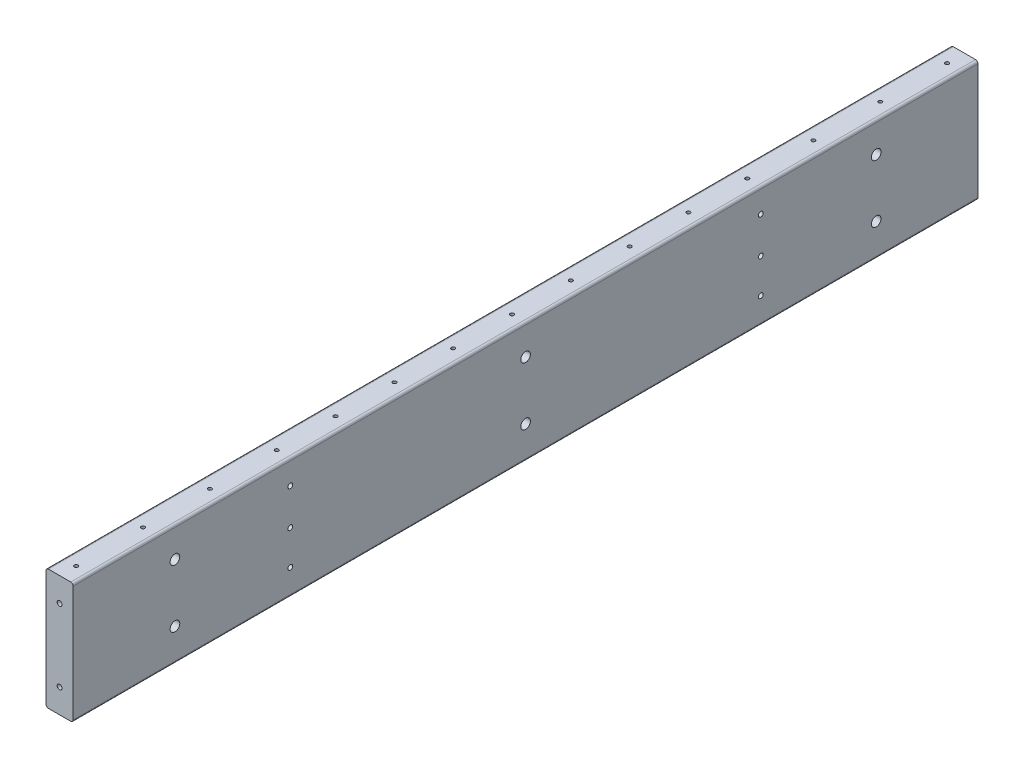
SolidWorks part; units mm, degrees
ref_plane "Front Plane" through (0, 0, 0) normal (0, 0, 1) x (1, 0, 0)
ref_plane "Top Plane" through (0, 0, 0) normal (0, 1, 0) x (1, 0, 0)
ref_plane "Right Plane" through (0, 0, 0) normal (1, 0, 0) x (0, 0, -1)
ref_plane "Plane1" through (-31.1883, 0, 0) normal (-1, 0, 0) x (0, -1, 0)
sketch "Sketch1" plane through (-31.1883, 0, 0) normal (-1, 0, 0) x (0, -1, 0)
  line L0 (-134.2727, 0) -> (65.7273, 0)
  line L1 (65.7273, 0) -> (65.7273, 1500)
  line L2 (65.7273, 1500) -> (-134.2727, 1500)
  line L3 (-134.2727, 1500) -> (-134.2727, 0)
extrude "Boss-Extrude1" add sketch "Sketch1" against normal blind 45
hole_wizard "Ø6.0 (6) Diameter Hole1" positions "Sketch3" profile "Sketch2" hole size "Ø6.0" standard "ANSI Metric"
sketch "Sketch3" plane through (0, 134.2727, 0) normal (0, 1, 0) x (1, 0, 0)
  point P0 (-8.6883, -750)
  point P1 (-8.6883, -457.5)
  point P2 (-8.6883, -555)
  point P3 (-8.6883, -652.5)
  point P4 (-8.6883, -847.5)
  point P5 (-8.6883, -945)
  point P6 (-8.6883, -1042.5)
  point P7 (-8.6883, -139.63)
  point P8 (-8.6883, -250.49)
  point P9 (-8.6883, -1250.8649)
  point P10 (-8.6883, -1361.7249)
  point P11 (-8.6883, -28.77)
  point P12 (-8.6883, -360)
  point P13 (-8.6883, -1140)
  point P14 (-8.6883, -1472.5849)
sketch "Sketch2" plane through (-8.6883, 134.2727, 750) normal (1, 0, 0) x (0, 0, 1)
  line L0 (0, 0) -> (0, 18)
  line L1 (0, 18) -> (3, 16.1974)
  line L2 (3, 16.1974) -> (3, 0)
  line L5 (3, 0) -> (0, 0)
  line L10 (0, 18) -> (-3, 16.1974) construction
  line L11 (0, -6.35) -> (0, 107.95) construction
  dimension "Hole Dia." = 6
  dimension "Hole Depth" = 16.1974
  dimension "Drill Angle" = 118
hole_wizard "Ø6.0 (6) Diameter Hole2" positions "Sketch5" profile "Sketch4" hole size "Ø6.0" standard "ANSI Metric"
sketch "Sketch5" plane through (0, -65.7273, 0) normal (0, -1, 0) x (-1, 0, 0)
  point P0 (8.6883, -750)
  point P1 (8.6883, -457.5)
  point P2 (8.6883, -555)
  point P3 (8.6883, -652.5)
  point P4 (8.6883, -847.5)
  point P5 (8.6883, -945)
  point P6 (8.6883, -1042.5)
  point P7 (8.6883, -139.63)
  point P8 (8.6883, -250.49)
  point P9 (8.6883, -1250.8649)
  point P10 (8.6883, -1361.7249)
  point P11 (8.6883, -28.77)
  point P12 (8.6883, -360)
  point P13 (8.6883, -1140)
  point P14 (8.6883, -1472.5849)
sketch "Sketch4" plane through (-8.6883, -65.7273, 750) normal (1, 0, 0) x (0, 0, -1)
  line L0 (0, 0) -> (0, 18)
  line L1 (0, 18) -> (3, 16.1974)
  line L2 (3, 16.1974) -> (3, 0)
  line L5 (3, 0) -> (0, 0)
  line L10 (0, 18) -> (-3, 16.1974) construction
  line L11 (0, -6.35) -> (0, 107.95) construction
  dimension "Hole Dia." = 6
  dimension "Hole Depth" = 16.1974
  dimension "Drill Angle" = 118
hole_wizard "Ø8.0 (8) Diameter Hole1" positions "Sketch7" profile "Sketch6" hole size "Ø8.0" standard "ANSI Metric"
sketch "Sketch7" plane through (-31.1883, 0, 0) normal (-1, 0, 0) x (0, 0, 1)
  point P0 (1140, -22.7273)
  point P1 (1140, 34.2727)
  point P2 (1140, 94.2727)
  point P3 (360, -22.7273)
  point P4 (360, 34.2727)
  point P5 (360, 94.2727)
sketch "Sketch6" plane through (-31.1883, -22.7273, 1140) normal (0, 1, 0) x (0, 0, 1)
  line L0 (0, 0) -> (0, 45)
  line L1 (0, 45) -> (4, 45)
  line L2 (4, 45) -> (4, 0)
  line L5 (4, 0) -> (0, 0)
  line L11 (0, -6.35) -> (0, 107.95) construction
  dimension "Thru Hole Dia." = 8
  dimension "Thru Hole Depth" = 45
hole_wizard "Ø16.0 (16) Diameter Hole1" positions "Sketch9" profile "Sketch8" hole size "Ø16.0" standard "ANSI Metric"
sketch "Sketch9" plane through (13.8117, 0, 0) normal (1, 0, 0) x (0, 0, -1)
  point P0 (-1331.25, -11.7273)
  point P1 (-1331.25, 84.2727)
  point P2 (-750, -11.7273)
  point P3 (-750, 84.2727)
  point P4 (-168.75, -11.7273)
  point P5 (-168.75, 84.2727)
sketch "Sketch8" plane through (13.8117, -11.7273, 1331.25) normal (0, 1, 0) x (0, 0, -1)
  line L0 (0, 0) -> (0, 45)
  line L1 (0, 45) -> (8, 45)
  line L2 (8, 45) -> (8, 0)
  line L5 (8, 0) -> (0, 0)
  line L11 (0, -6.35) -> (0, 107.95) construction
  dimension "Thru Hole Dia." = 16
  dimension "Thru Hole Depth" = 45
hole_wizard "Ø8.0 (8) Diameter Hole2" positions "Sketch11" profile "Sketch10" hole size "Ø8.0" standard "ANSI Metric"
sketch "Sketch11" plane through (0, 0, 0) normal (0, 0, -1) x (-1, 0, 0)
  point P0 (8.6883, 94.2727)
sketch "Sketch10" plane through (-8.6883, 94.2727, 0) normal (1, 0, 0) x (0, 1, 0)
  line L0 (0, 0) -> (0, 1532.4501)
  line L1 (0, 1532.4501) -> (4, 1532.4501)
  line L2 (4, 1532.4501) -> (4, 0)
  line L5 (4, 0) -> (0, 0)
  line L10 (0, 1532.4501) -> (-4, 1532.4501) construction
  line L11 (0, -6.35) -> (0, 107.95) construction
  dimension "Hole Dia." = 8
  dimension "Hole Depth" = 1532.4501
  dimension "Drill Angle" = 180
hole_wizard "M33 Clearance Hole1" positions "Sketch13" profile "Sketch12" hole size "M33" standard "ANSI Metric"
sketch "Sketch13" plane through (-31.1883, 0, 0) normal (-1, 0, 0) x (0, 0, 1)
  point P0 (50, -22.7273)
  point P1 (50, 94.2727)
  point P2 (1450, -22.7273)
  point P3 (1450, 94.2727)
sketch "Sketch12" plane through (-31.1883, -22.7273, 50) normal (0, 1, 0) x (0, 0, 1)
  line L0 (0, 0) -> (0, 30)
  line L1 (0, 30) -> (18, 30)
  line L2 (18, 30) -> (18, 0)
  line L5 (18, 0) -> (0, 0)
  line L10 (0, 30) -> (-18, 30) construction
  line L11 (0, -6.35) -> (0, 107.95) construction
  dimension "Hole Dia." = 36
  dimension "Hole Depth" = 30
  dimension "Drill Angle" = 180
hole_wizard "Ø8.0 (8) Diameter Hole3" positions "Sketch15" profile "Sketch14" hole size "Ø8.0" standard "ANSI Metric"
sketch "Sketch15" plane through (0, 0, 0) normal (0, 0, -1) x (-1, 0, 0)
  point P0 (8.6883, -25.7273)
sketch "Sketch14" plane through (-8.6883, -25.7273, 0) normal (1, 0, 0) x (0, 1, 0)
  line L0 (0, 0) -> (0, 1533.4169)
  line L1 (0, 1533.4169) -> (4, 1533.4169)
  line L2 (4, 1533.4169) -> (4, 0)
  line L5 (4, 0) -> (0, 0)
  line L10 (0, 1533.4169) -> (-4, 1533.4169) construction
  line L11 (0, -6.35) -> (0, 107.95) construction
  dimension "Hole Dia." = 8
  dimension "Hole Depth" = 1533.4169
  dimension "Drill Angle" = 180
chamfer "Chamfer1" distance 0.025 angle 45 10 edges at (-31.1883, -22.7273, 1144) (-31.1883, 94.2727, 364) (-31.1883, 34.2727, 364) (-12.6883, -25.7273, 0) (-4.6883, 94.2727, 1500) (-4.6883, -25.7273, 1500) (-31.1883, -22.7273, 364) (-31.1883, 34.2727, 1144) (-12.6883, 94.2727, 0) (-31.1883, 94.2727, 1144)
fillet "Fillet1" radius 4 4 edges at (-31.1883, -65.7273, 750) (13.8117, 134.2727, 750) (13.8117, -65.7273, 750) (-31.1883, 134.2727, 750)
